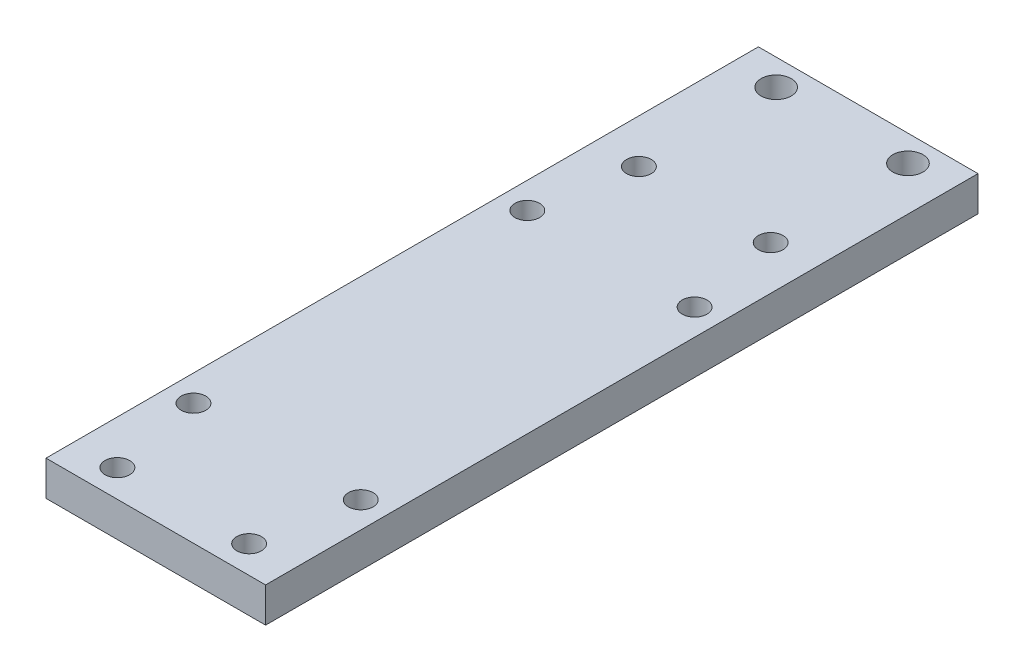
SolidWorks part; units mm, degrees
material "6061 Alloy"
ref_plane "Front Plane" through (0, 0, 0) normal (0, 0, 1) x (1, 0, 0)
ref_plane "Top Plane" through (0, 0, 0) normal (0, 1, 0) x (1, 0, 0)
ref_plane "Right Plane" through (0, 0, 0) normal (1, 0, 0) x (0, 0, -1)
sketch "Sketch1" plane through (0, 0, 0) normal (0, 1, 0) x (1, 0, 0)
  line L1 (-20, 80) -> (20, 80)
  line L2 (-20, 80) -> (-20, -80)
  line L3 (-20, -80) -> (20, -80)
  line L4 (20, 80) -> (20, -80)
  line L5 (0, -80) -> (0, 80) construction
  line L6 (-20, 0) -> (20, 0) construction
  point P0 (0, 0)
  dimension "D1" = 40
  dimension "D2" = 160
extrude "Boss-Extrude1" add sketch "Sketch1" along normal mid plane 6.35
sketch "Sketch3" plane through (0, 0, 0) normal (0, 1, 0) x (1, 0, 0)
  line L0 (0, 75.2375) -> (12, 75.2375) construction
  line L5 (0, -80) -> (0, 80) construction
  line L6 (-20, 0) -> (20, 0) construction
  line L7 (0, 50.2375) -> (12, 50.2375) construction
  line L8 (20, 80) -> (-20, 80) construction
  line L9 (-20, 80) -> (-20, -80) construction
  line L10 (-20, -80) -> (20, -80) construction
  line L11 (20, -80) -> (20, 80) construction
  circle A0 centre (12, 75.2375) radius 2.75
  circle A1 centre (12, 50.2375) radius 2.25
  circle A2 centre (-12, 50.2375) radius 2.25
  circle A3 centre (-12, 75.2375) radius 2.75
  circle A4 centre (-12, -44.7625) radius 2.25
  circle A5 centre (12, -44.7625) radius 2.25
  point P0 (0, 0)
  dimension "D4" = 5.5
  dimension "D5" = 4.5
  dimension "D1" = 4.7625
  dimension "D2" = 25
  dimension "D3" = 12
  dimension "D6" = 2
extrude "M4/5_through" cut sketch "Sketch3" against normal up to surface (3.175 mm away) and the other way blind 6.35 up to face at (0, -3.175, 0)
sketch "Sketch4" plane through (0, 0, -80) normal (0, 0, -1) x (-1, 0, 0)
  circle A0 centre (0, 0) radius 1.5
  dimension "D1" = 3
extrude "M3_DRILL" cut sketch "Sketch4" against normal blind 8
sketch "Sketch5" plane through (0, 3.175, 0) normal (0, 1, 0) x (1, 0, 0)
  line L0 (-12, -44.7625) -> (0, -44.7625) construction
  line L2 (0, 0) -> (0, -23.6676) construction
  line L3 (-12, 50.2375) -> (-12, -44.7625) construction
  line L4 (-12, 2.7375) -> (-1.1233, 2.7375) construction
  line L5 (-20, 80) -> (-20, -80) construction
  circle A0 centre (-15.2375, -27.6625) radius 2.25
  circle A1 centre (15.2375, -27.6625) radius 2.25
  circle A2 centre (15.2375, 33.1375) radius 2.25
  circle A3 centre (-15.2375, 33.1375) radius 2.25
  circle A4 centre (-12, -44.7625) radius 2.25 construction
  circle A6 centre (-12, 50.2375) radius 2.25 construction
  dimension "D2" = 4.5
  dimension "D1" = 17.1
  dimension "D3" = 4.7625
extrude "M4_through" cut sketch "Sketch5" against normal up to surface (6.35 mm away) up to face at (12, -3.175, 47.0125)
sketch "Sketch6" plane through (0, 3.175, 0) normal (0, 1, 0) x (1, 0, 0)
  line L0 (-12, -44.7625) -> (12, -44.7625) construction
  line L2 (20, -80) -> (20, 80) construction
  line L3 (-20, -80) -> (20, -80)
  line L4 (-20, -80) -> (-20, -49.7625)
  line L5 (-20, -49.7625) -> (20, -49.7625)
  line L6 (20, -80) -> (20, -49.7625)
  line L7 (0, -49.7625) -> (0, -80) construction
  line L8 (-20, -64.8812) -> (20, -64.8812) construction
  point P220 (0, -64.8812)
  dimension "D1" = 5
extrude "Cut-Extrude1" cut sketch "Sketch6" against normal up to surface (6.35 mm away) up to face at (-15.2375, -3.175, -30.8875)
